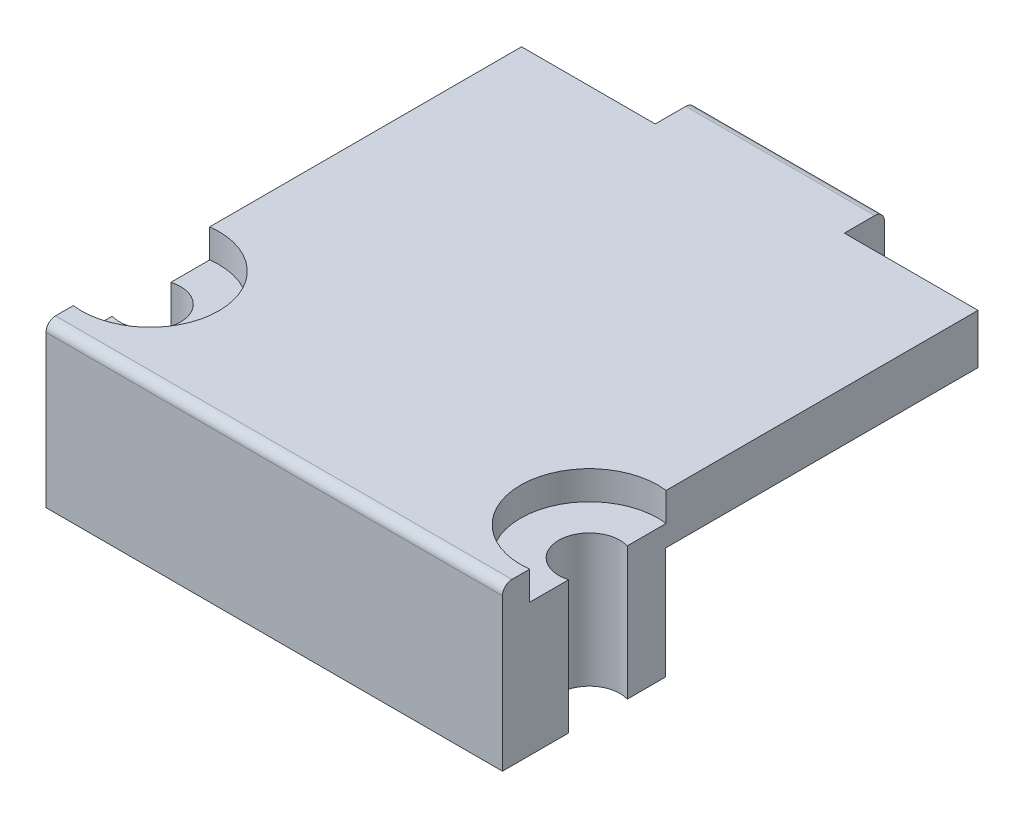
SolidWorks part; units mm, degrees
ref_plane "Front Plane" through (0, 0, 0) normal (0, 0, 1) x (1, 0, 0)
ref_plane "Top Plane" through (0, 0, 0) normal (0, 1, 0) x (1, 0, 0)
ref_plane "Right Plane" through (0, 0, 0) normal (1, 0, 0) x (0, 0, -1)
sketch "Sketch1" plane through (0, 0, 0) normal (0, 1, 0) x (1, 0, 0)
  line L0 (-11.95, 12.45) -> (-11.95, -12.45)
  line L1 (-11.95, -12.45) -> (11.95, -12.45)
  line L2 (11.95, -12.45) -> (11.95, 12.45)
  line L3 (11.95, 12.45) -> (4.95, 12.45)
  line L4 (4.95, 12.45) -> (4.95, 14.55)
  line L5 (4.95, 14.55) -> (-4.95, 14.55)
  line L6 (-4.95, 14.55) -> (-4.95, 12.45)
  line L7 (-4.95, 12.45) -> (-11.95, 12.45)
  point P4 (11.95, 0)
  point P9 (0, -12.45)
  point P11 (-4.6376, 12.45)
  point P12 (0, 14.55)
  dimension "D1" = 23.9
  dimension "D2" = 24.9
  dimension "D3" = 2.1
  dimension "D4" = 9.9
extrude "Boss-Extrude1" add sketch "Sketch1" along normal blind 2.6
sketch "Sketch2" plane through (0, 0, 0) normal (0, -1, 0) x (1, 0, 0)
  line L1 (-11.95, 10.45) -> (11.95, 10.45)
  line L2 (-11.95, 10.45) -> (-11.95, 12.45)
  line L3 (-11.95, 12.45) -> (11.95, 12.45)
  line L4 (11.95, 10.45) -> (11.95, 12.45)
  line L5 (-11.95, 10.45) -> (11.95, 12.45) construction
  line L6 (-11.95, 12.45) -> (11.95, 10.45) construction
  point P0 (0, 11.45)
  point P5 (0, 0)
  point P6 (0, 10.45)
  dimension "D1" = 2
extrude "Boss-Extrude2" add sketch "Sketch2" along normal blind 5.85
sketch "Sketch3" plane through (0, 2.6, 0) normal (0, 1, 0) x (1, 0, 0)
  line L0 (0, -12.45) -> (0, -7.45) construction
  line L1 (-11.95, -12.45) -> (11.95, -12.45) construction
  line L2 (-11.5, -7.45) -> (11.5, -7.45) construction
  circle A0 centre (-11.5, -7.45) radius 1.6
  circle A1 centre (11.5, -7.45) radius 1.6
  point P11 (0, -5.2327)
  point P12 (0, 0)
  point P13 (0, 0)
  point P14 (0, -7.45)
  dimension "D1" = 3.2
  dimension "D2" = 23
  dimension "D3" = 5
extrude "Cut-Extrude1" cut sketch "Sketch3" against normal up to next
sketch "Sketch4" plane through (0, 0, 0) normal (0, -1, 0) x (1, 0, 0)
  line L0 (-11.95, 8.9854) -> (-11.95, 10.45) construction
  line L1 (-11.95, -12.45) -> (-11.95, 5.9146) construction
  line L2 (-11.95, 5.9146) -> (-11.95, 3.9146)
  line L3 (-11.95, 10.9854) -> (-11.95, 8.9854)
  line L4 (0, 10.45) -> (0, 0) construction
  line L5 (-11.95, 10.45) -> (11.95, 10.45) construction
  line L6 (11.95, 10.9854) -> (11.95, 8.9854)
  line L7 (11.95, 5.9146) -> (11.95, 3.9146)
  arc A0 (-11.95, 10.9854) -> (-11.95, 3.9146) centre (-11.5, 7.45) cw
  arc A1 (-11.95, 5.9146) -> (-11.95, 8.9854) centre (-11.5, 7.45) ccw construction
  arc A2 (-11.95, 5.9146) -> (-11.95, 8.9854) centre (-11.5, 7.45) ccw
  arc A3 (11.95, 5.9146) -> (11.95, 8.9854) centre (11.5, 7.45) cw
  arc A4 (11.95, 10.9854) -> (11.95, 3.9146) centre (11.5, 7.45) ccw
  dimension "D1" = 2
extrude "Boss-Extrude3" add sketch "Sketch4" along normal up to surface (5.85 mm away) up to face at (0, -5.85, 11.45)
sketch "Sketch5" plane through (0, -5.85, 0) normal (0, -1, 0) x (1, 0, 0)
  line L0 (-11.95, 8.9854) -> (-11.95, 5.9146) construction
  line L1 (-8.4361, 6.35) -> (-7.4361, 6.35)
  line L2 (-8.4361, 6.35) -> (-8.4361, 8.55)
  line L3 (-8.4361, 8.55) -> (-7.4361, 8.55)
  line L4 (-7.4361, 6.35) -> (-7.4361, 8.55)
  line L5 (-8.4361, 6.35) -> (-7.4361, 8.55) construction
  line L6 (-8.4361, 8.55) -> (-7.4361, 6.35) construction
  arc A0 (-11.95, 3.9146) -> (-9.576, 10.45) centre (-11.5, 7.45) ccw construction
  arc A1 (-11.95, 3.9146) -> (-9.576, 10.45) centre (-11.5, 7.45) ccw construction
  point P0 (-7.9361, 7.45)
  point P11 (-11.95, 7.45)
  dimension "D1" = 2.2
  dimension "D2" = 1
extrude "Cut-Extrude2" cut sketch "Sketch5" against normal blind 2.1 contours L4 L3 L2 L1
sketch "Sketch6" plane through (0, 2.6, 0) normal (0, 1, 0) x (1, 0, 0)
  circle A0 centre (11.5, -7.45) radius 3.6
  circle A1 centre (-11.5, -7.45) radius 3.6
  arc A2 (-11.95, -8.9854) -> (-11.95, -5.9146) centre (-11.5, -7.45) ccw construction
  arc A3 (11.95, -5.9146) -> (11.95, -8.9854) centre (11.5, -7.45) ccw construction
  dimension "D1" = 7.2
  dimension "D2" = 7.2
extrude "Cut-Extrude3" cut sketch "Sketch6" against normal blind 1.5
fillet "Fillet1" radius 0.5 2 edges at (0, 2.6, -14.55) (0, 2.6, 12.45)
